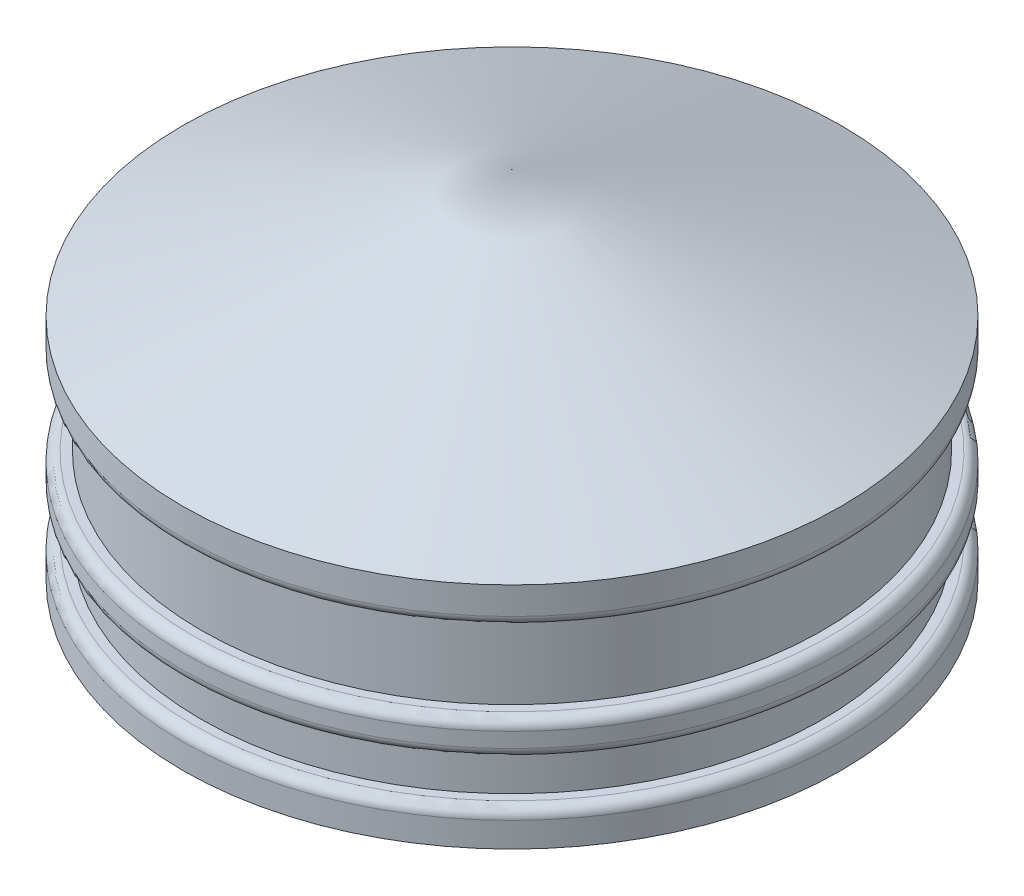
SolidWorks part; units mm, degrees
ref_plane "Front Plane" through (0, 0, 0) normal (0, 0, 1) x (1, 0, 0)
ref_plane "Top Plane" through (0, 0, 0) normal (0, 1, 0) x (1, 0, 0)
ref_plane "Right Plane" through (0, 0, 0) normal (1, 0, 0) x (0, 0, -1)
sketch "Sketch2" plane through (0, 0, 0) normal (1, 0, 0) x (0, 0, -1)
  line L0 (0, 14.3) -> (13.25, 9.2)
  line L1 (13.25, 9.2) -> (13.25, 0)
  line L2 (13.25, 0) -> (8.15, 0)
  line L3 (8.15, 0) -> (8.15, 3.5)
  line L4 (8.15, 3.5) -> (9.75, 3.5)
  line L5 (9.75, 3.5) -> (9.75, 6.7969)
  line L6 (9.75, 6.7969) -> (0, 10.5497)
  line L7 (0, 10.5497) -> (0, 14.3)
  line L8 (9.75, 3.5) -> (13.25, 3.5) construction
  line L9 (0, 10.5497) -> (1.2573, 13.8161) construction
  dimension "D1" = 5.1
  dimension "D2" = 9.2
  dimension "D3" = 13.25
  dimension "D4" = 5.1
  dimension "D5" = 3.5
ref_axis "Axis1" through (0, -0.715, 0) along (0, 1, 0)
revolve "Revolve1" add sketch "Sketch2" angle 360 about axis through (0, -0.715, 0) along (0, 1, 0)
ref_plane "Plane1" through (0, 1.4, 0) normal (0, 1, 0) x (1, 0, 0)
sketch "Sketch3" plane through (0, 1.4, 0) normal (0, 1, 0) x (1, 0, 0)
  circle A0 centre (0, 0) radius 13.25 construction
  circle A1 centre (0, 0) radius 13.25
  circle A2 centre (0, 0) radius 12.5
  dimension "D1" = 0.75
extrude "Cut-Extrude1" cut sketch "Sketch3" along normal blind 1.7
ref_plane "Plane2" through (0, 4.5, 0) normal (0, 1, 0) x (1, 0, 0)
sketch "Sketch4" plane through (0, 4.5, 0) normal (0, 1, 0) x (1, 0, 0)
  circle A1 centre (0, 0) radius 12.5
  circle A2 centre (0, 0) radius 12.5
  circle A3 centre (0, 0) radius 13.25
  circle A4 centre (0, 0) radius 13.25
  dimension "D1" = 0
  dimension "D2" = 0
extrude "Cut-Extrude2" cut sketch "Sketch4" along normal blind 3.2
fillet "Fillet1" radius 0.4 4 edges at (0, 7.7, 13.25) (0, 4.5, 13.25) (0, 3.1, 13.25) (0, 1.4, 13.25)
ref_plane "Plane3" through (0, 9.2, 0) normal (0, -1, 0) x (-1, 0, 0)
